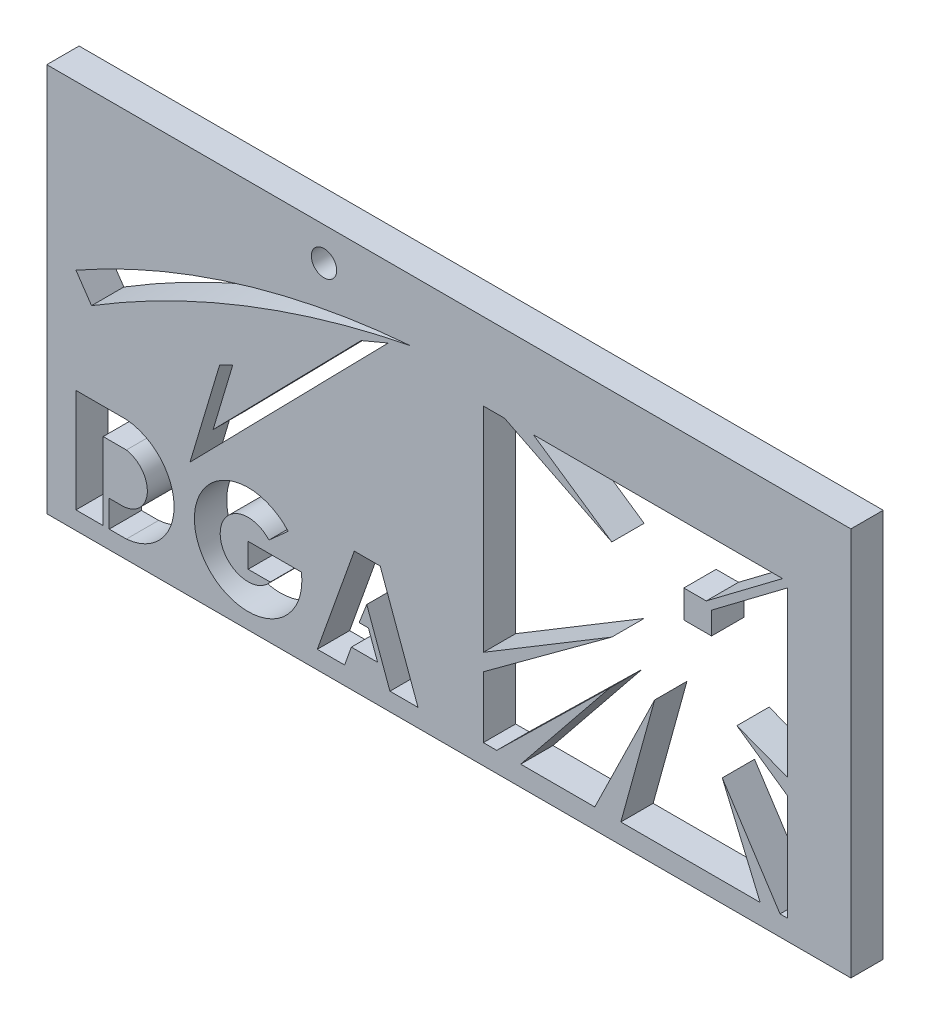
SolidWorks part; units mm, degrees
ref_plane "Front Plane" through (0, 0, 0) normal (0, 0, 1) x (1, 0, 0)
ref_plane "Top Plane" through (0, 0, 0) normal (0, 1, 0) x (1, 0, 0)
ref_plane "Right Plane" through (0, 0, 0) normal (1, 0, 0) x (0, 0, -1)
sketch "Sketch1" plane through (0, 0, 0) normal (0, 0, 1) x (1, 0, 0)
  line L0 (85.3333, 264) -> (426.6667, 264) construction
  line L1 (-9.0234, 115.4931) -> (239.9616, 115.4931)
  line L2 (-9.0234, 115.4931) -> (-9.0234, -4.9399)
  line L3 (-9.0234, -4.9399) -> (239.9616, -4.9399)
  line L4 (239.9616, 115.4931) -> (239.9616, -4.9399)
  line L5 (0, 64.8979) -> (4.8346, 57.7982)
  line L6 (44.5094, 61.7657) -> (35.3216, 31.0699)
  line L7 (35.3216, 31.0699) -> (96.6598, 93.6783)
  line L8 (96.6598, 93.6783) -> (88.3288, 90.1792)
  line L9 (88.3288, 90.1792) -> (42.4615, 43.3622)
  line L10 (42.4615, 43.3622) -> (48.5649, 63.7531)
  line L11 (48.5649, 63.7531) -> (44.5094, 61.7657)
  line L12 (15.6212, 32.654) -> (0, 32.654)
  line L13 (0, 32.654) -> (0, 0.602)
  line L14 (0, 0.602) -> (8.4298, 0.602)
  line L15 (15.6212, 24.4902) -> (8.4298, 24.4902)
  line L16 (8.4298, 24.4902) -> (8.4298, 8.985)
  line L17 (10.294, 8.8619) -> (14.2747, 8.8619)
  line L18 (53.3137, 18.8301) -> (69.8126, 18.8301)
  line L19 (53.3137, 18.8301) -> (53.3137, 11.3462)
  line L20 (53.3137, 11.3462) -> (60.1637, 11.3462)
  line L21 (65.7173, 27.7283) -> (59.7593, 22.3963)
  line L22 (74.7422, 0.602) -> (86.192, 32.654)
  line L23 (86.192, 32.654) -> (94.2152, 32.654)
  line L24 (94.2152, 32.654) -> (105.9157, 0.602)
  line L25 (105.9157, 0.602) -> (97.2239, 0.602)
  line L26 (97.2239, 0.602) -> (95.0912, 6.4442)
  line L27 (93.406, 6.4442) -> (85.2726, 6.4442)
  line L28 (85.2726, 6.4442) -> (83.1857, 0.602)
  line L29 (83.1857, 0.602) -> (74.7422, 0.602)
  line L33 (95.0912, 6.4442) -> (90.045, 20.2676)
  line L34 (90.045, 20.2676) -> (87.6961, 14.2191)
  line L35 (87.6961, 14.2191) -> (90.5677, 14.2191)
  line L36 (90.5677, 14.2191) -> (93.406, 6.4442)
  line L37 (8.4298, 8.985) -> (8.4298, 0.602)
  line L38 (10.294, 8.8619) -> (10.294, 0.602)
  line L39 (10.294, 0.602) -> (15.6212, 0.602)
  line L40 (339.4812, 160.6847) -> (1192.8145, 160.6847) construction
  line L41 (141.6238, 91.5963) -> (191.5212, 91.5963)
  line L42 (220.3533, 89.8689) -> (220.3533, 70.4862)
  line L43 (220.3533, 39.0508) -> (204.6522, 45.0709)
  line L44 (204.6522, 45.0709) -> (220.3533, 34.1089)
  line L45 (220.3533, 34.1089) -> (220.3533, 1.2757)
  line L46 (220.3533, 1.2757) -> (218.022, 1.2757)
  line L47 (218.022, 1.2757) -> (200.1245, 28.8059)
  line L48 (200.1245, 28.8059) -> (211.8662, 1.2757)
  line L49 (211.8662, 1.2757) -> (168.7234, 1.2757)
  line L50 (168.7234, 1.2757) -> (179.1953, 39.2396)
  line L51 (179.1953, 39.2396) -> (160.6592, 1.2757)
  line L52 (160.6592, 1.2757) -> (137.7141, 1.2757)
  line L53 (137.7141, 1.2757) -> (165.3224, 35.5251)
  line L54 (165.3224, 35.5251) -> (130.297, 1.2757)
  line L55 (130.297, 1.2757) -> (126.1462, 1.2757)
  line L56 (126.1462, 1.2757) -> (126.1462, 20.2676)
  line L57 (126.1462, 20.2676) -> (165.9295, 49.4617)
  line L58 (165.9295, 49.4617) -> (126.1462, 25.4864)
  line L59 (126.1462, 25.4864) -> (126.1462, 91.5476)
  line L60 (126.1462, 91.5476) -> (132.7094, 91.5476)
  line L61 (132.7094, 91.5476) -> (165.9295, 74.9751)
  line L62 (165.9295, 74.9751) -> (141.6238, 91.5963)
  line L63 (191.5212, 73.7822) -> (191.5212, 91.5963)
  line L64 (188.2298, 65.1936) -> (196.8126, 65.1936)
  line L65 (188.2298, 65.1936) -> (188.2298, 73.7822)
  line L66 (188.2298, 73.7822) -> (191.5212, 73.7822)
  line L67 (196.8126, 65.1936) -> (196.8126, 68.4897)
  line L68 (193.5212, 73.7822) -> (193.5212, 91.5963)
  line L69 (196.8126, 70.4862) -> (220.3533, 70.4862)
  line L70 (196.8126, 68.4897) -> (220.3533, 68.4897)
  line L71 (192.5212, 73.7822) -> (192.5212, 78.0417) construction
  line L72 (196.8126, 69.4879) -> (202.046, 69.4879) construction
  line L73 (196.8126, 70.4862) -> (196.8126, 73.7822)
  line L74 (193.5212, 73.7822) -> (196.8126, 73.7822)
  line L75 (220.3533, 68.4897) -> (220.3533, 39.0508)
  line L76 (193.5212, 91.5963) -> (218.813, 91.5963)
  line L77 (179.1953, 59.9506) -> (208.066, 64.8979) construction
  line L78 (195.1669, 73.7822) -> (218.813, 91.5963)
  line L79 (196.8126, 72.1342) -> (220.3533, 89.8689)
  line L80 (191.5212, 73.7822) -> (193.5212, 73.7822)
  line L81 (196.8126, 70.4862) -> (196.8126, 68.4897)
  line L82 (191.5212, 91.5963) -> (193.5212, 91.5963)
  line L83 (220.3533, 70.4862) -> (220.3533, 68.4897)
  arc A0 (0, 64.8979) -> (103.6041, 96.429) centre (123.3558, -154.4462) cw
  arc A1 (4.8346, 57.7982) -> (103.6041, 96.429) centre (160.6592, -195.0274) cw
  circle A2 centre (76.8133, 105.1795) radius 3.9276
  arc A3 (15.6212, 24.4902) -> (14.2747, 8.8619) centre (14.2333, 16.7376) cw
  arc A4 (15.6212, 32.654) -> (15.6212, 0.602) centre (14.3088, 16.628) cw
  arc A5 (65.7173, 27.7283) -> (69.8126, 18.8301) centre (53.3137, 16.628) ccw
  arc A6 (59.7593, 22.3963) -> (60.1637, 11.3462) centre (53.3137, 16.628) ccw
  text T0 "UNIVERSITÉ"
  text T1 "DE TOULON"
  dimension "D1" = 1.9965
  dimension "D2" = 2
extrude "Boss-Extrude1" add sketch "Sketch1" along normal blind 10 contours L4 L1 L2 L3 A2 A1 L5 A0 L11 L10 L9 L8 L7 L6 L35 L36 L27 L28 L29 L22 L23 L24 L25 L26 L33 L34 L61 L62 L41 L42 L43 L44 L45 L46 L47 L48 L49 L50 L51 L52 L53 L54 L55 L56 L57 L58 | L64 L67 L66 L65
